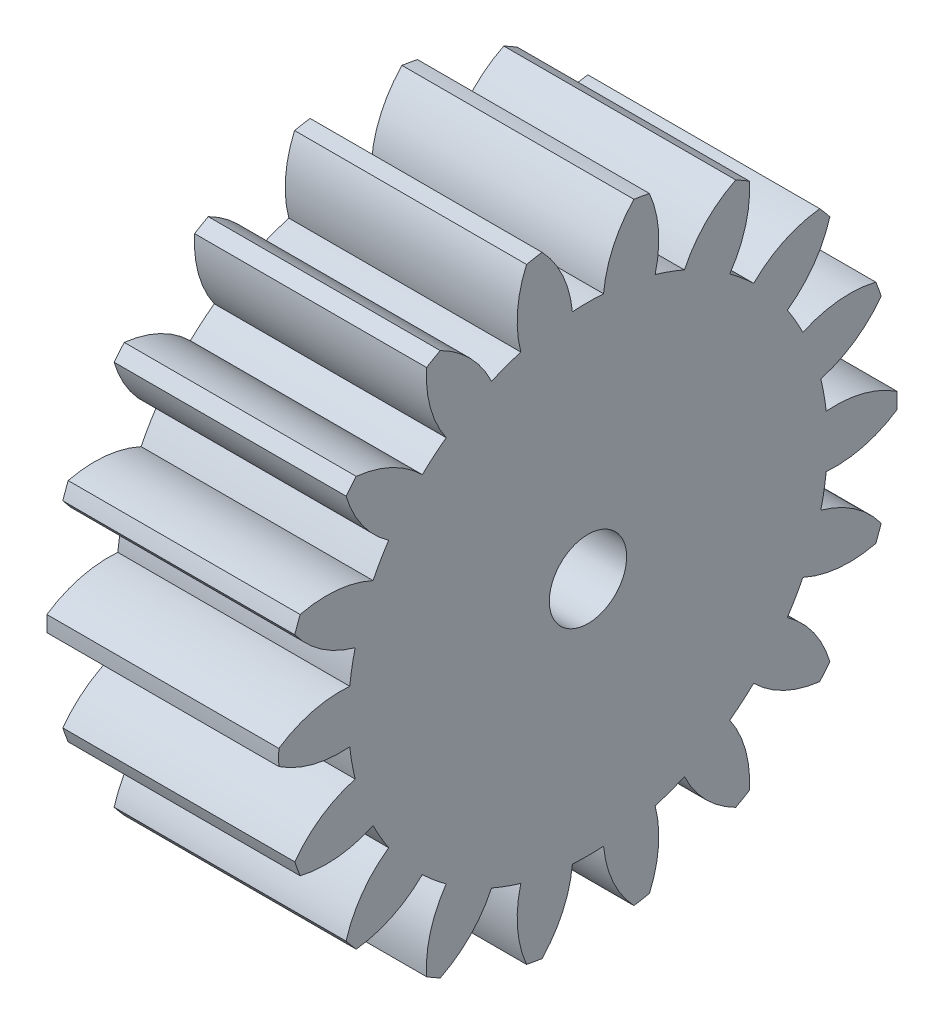
SolidWorks part; units mm, degrees
ref_plane "Plane1" through (0, 0, 0) normal (0, 0, 1) x (1, 0, 0)
ref_plane "Plane2" through (0, 0, 0) normal (0, 1, 0) x (1, 0, 0)
ref_plane "Plane3" through (0, 0, 0) normal (1, 0, 0) x (0, 0, -1)
other "Configuration Table"
sketch "HoldingSke" plane through (0, 0, 0) normal (0, 1, 0) x (1, 0, 0)
  line L0 (0, 0) -> (0.4755, -0.1545)
  line L1 (-15, 0) -> (100, 0) construction
  line L2 (0, 0) -> (-2.1039, 2.3779)
  line L3 (0, 0) -> (-11.863, 4.5341)
  line L4 (0, 0) -> (8.2133, 2.6687)
  line L5 (0, 0) -> (-46.8476, -17.4728)
  line L6 (0, 0) -> (-12.4344, -8.3896)
  line L7 (-2.1039, 2.3779) -> (8.6586, 51.2059)
  line L8 (-76.2, 54.61) -> (-75.3, 54.61)
  line L9 (-71.009, 38.7566) -> (-53.1078, 45.2721)
  line L10 (-76.2, 71.12) -> (104.1128, 71.12)
  line L11 (0, 0) -> (-15, 0)
  line L12 (-76.2, 101.6) -> (-76.133, 101.6)
  line L13 (24.9733, 27.94) -> (52.9518, 28.4284)
  line L14 (24.9733, 27.94) -> (24.9743, 27.94)
  line L15 (24.9733, 27.94) -> (100.4006, 29.5858)
  line L16 (-63.627, -2) -> (-12.827, -2)
  circle A0 centre (0, 0) radius 2.5
  circle A1 centre (0, 0) radius 15.499
  circle A2 centre (0, 0) radius 37.5
  circle A3 centre (0, 0) radius 2.5
  dimension "MHD" = 30.998
  dimension "Hub_dia" = 75
  dimension "Bore" = 5
  dimension "MBD" = 5
  dimension "Num_teeth" = 18
  dimension "Pitch" = 0.5
  dimension "Overall_len" = 50
  dimension "Show_teeth" = 18
  dimension "Thickness" = 15
  dimension "OAL" = 50.0001
  dimension "T_dim" = 0.9
  dimension "Ap" = 20
  dimension "H" = 19.05
  dimension "Pitch_radius" = 180.3128
  dimension "Width" = 15
  dimension "Backlash" = 0.067
  dimension "Addendum_fac" = 1
  dimension "Dedendum_fac" = 1.25
  dimension "Clearance_fac" = 0.25
  dimension "Dedendum_add" = 0.001
  dimension "Module" = 2
sketch "BasProSke" plane through (0, 0, 0) normal (0, 1, 0) x (1, 0, 0)
  line L0 (-10, 0) -> (60, 0) construction
  line L1 (0, 0) -> (0, 20)
  line L2 (0, 0) -> (15, 0)
  line L3 (15, 0) -> (15, 20)
  line L4 (15, 20) -> (0, 20)
  dimension "Thickness" = 15
  dimension "Diameter" = 40
revolve "Base-Revolve" add sketch "BasProSke" angle 360 about L0
sketch "TooCutSke" plane through (0, 0, 0) normal (1, 0, 0) x (0, 0, -1)
  line L1 (0, 0) -> (0, 107) construction
  line L2 (0, 0) -> (-1.686, 17.9209) construction
  line L3 (0, 0) -> (-6.231, 35.3376) construction
  line L4 (-1.686, 17.9209) -> (-3.1155, 17.6688) construction
  arc A0 (1.0078, 15.4662) -> (-1.0078, 15.4662) centre (0, 0) ccw
  arc A1 (2.9913, 19.8007) -> (-2.9913, 19.8007) centre (0, 0) ccw
  circle A2 centre (0, 0) radius 18 construction
  circle A3 centre (0, 0) radius 16.9145 construction
  arc A4 (-1.0078, 15.4662) -> (-2.9913, 19.8007) centre (-8.1775, 14.8063) ccw
  arc A5 (2.9913, 19.8007) -> (1.0078, 15.4662) centre (8.1775, 14.8063) ccw
  dimension "Root_dia" = 30.998
  dimension "Overcut_dia" = 40.0508
  dimension "Pitch_dia" = 36
  dimension "Base_dia" = 33.8289
  dimension "Flank_rad" = 7.2
  dimension "Half_ang" = 10
  dimension "Half_CT" = 1.4516
extrude "ToothCut" cut sketch "TooCutSke" along normal through all
fillet "Breaks" [suppressed] radius 0.04
fillet "RootFillets" [suppressed] radius 0.501
pattern_circular "TeethCuts" count 18 every 20 about axis through (-10, 0, 0) along (1, 0, 0) of "ToothCut", "RootFillets", "Breaks"
sketch "HubNeaOneSke" plane through (0, 0, 0) normal (-1, 0, 0) x (0, 0, 1)
  circle A0 centre (0, 0) radius 15.499
  dimension "Diameter" = 30.998
extrude "HubNearOne" [suppressed] add sketch "HubNeaOneSke" along normal blind 35.0001
sketch "HubNeaBotSke" plane through (0, 0, 0) normal (-1, 0, 0) x (0, 0, 1)
  circle A0 centre (0, 0) radius 15.499
  dimension "Diameter" = 30.998
extrude "HubNearBoth" [suppressed] add sketch "HubNeaBotSke" along normal blind 17.5
ref_plane "FarPln" through (15, 0, 0) normal (1, 0, 0) x (0, 0, -1)
sketch "HubFarSke" plane through (15, 0, 0) normal (1, 0, 0) x (0, 0, -1)
  circle A0 centre (0, 0) radius 15.499
  dimension "Diameter" = 30.998
extrude "HubFar" [suppressed] add sketch "HubFarSke" along normal blind 17.5
sketch "BorSke" plane through (0, 0, 0) normal (1, 0, 0) x (0, 0, -1)
  circle A0 centre (0, 0) radius 2.5
  dimension "Diameter" = 5
extrude "Bore" cut sketch "BorSke" along normal mid plane 100.0001
sketch "KeySke" plane through (0, 0, 0) normal (1, 0, 0) x (0, 0, -1)
  line L0 (-1, 0) -> (-1, 3.4)
  line L1 (-1, 3.4) -> (1, 3.4)
  line L2 (1, 3.4) -> (1, 0)
  line L3 (0, 0) -> (0, 34) construction
  line L4 (-1, 0) -> (1, 0)
  dimension "Offset" = 3.4
  dimension "Width" = 2
extrude "Keyway" [suppressed] cut sketch "KeySke" along normal mid plane 100.0001
pattern_circular "Keyway2" [suppressed] count 2 every 90 about axis through (-10, 0, 0) along (1, 0, 0)
equation "' \"Module@HoldingSke\" = 6.35"
equation "' \"Num_teeth@HoldingSke\" = 12"
equation "' \"Ap@HoldingSke\" =  20"
equation "' \"Ap@HoldingSke\" = 20"
equation "' \"Width@HoldingSke\" = 0.5 * 25.4"
equation "' \"Hub_dia@HoldingSke\"= 1 * 25.4"
equation "' \"Hub_dia@HoldingSke\" = 1 * 25.4"
equation "' \"Overall_len@HoldingSke\" = 1.0 * 25.4"
equation "' \"Bore@HoldingSke\" = 0.75 * 25.4"
equation "' \"T_dim@HoldingSke\" = 0.1 * 25.4"
equation "' \"Width@KeySke\" = 0.25 * 25.4"
equation "' \"Show_teeth@HoldingSke\" = 13"
equation "' \"Backlash@HoldingSke\" = 0.009 * 25.4"
equation "' \"Addendum_fac@HoldingSke\" = 1.0"
equation "' \"Dedendum_fac@HoldingSke\" = 1.25"
equation "' \"Dedendum_add@HoldingSke\" = 0.00005 * 25.4"
equation "' \"Clearance_fac@HoldingSke\" = 0.25"
equation "\"Pitch@HoldingSke\" = 1 / \"Module@HoldingSke\""
equation "\"Overcut_dia@TooCutSke\" = (\"Num_teeth@HoldingSke\" + 2 * \"Addendum_fac@HoldingSke\") / \"Pitch@HoldingSke\" + 0.002 * 25.4"
equation "\"Pitch_dia@TooCutSke\" = \"Num_teeth@HoldingSke\" / \"Pitch@HoldingSke\""
equation "\"Base_dia@TooCutSke\" = \"Num_teeth@HoldingSke\" / \"Pitch@HoldingSke\" * cos((\"Ap@HoldingSke\"  * 3.14159265 / 180))"
equation "\"Root_dia@TooCutSke\" = (\"Num_teeth@HoldingSke\" + 2) / \"Pitch@HoldingSke\" - 2 * (\"Addendum_fac@HoldingSke\" + \"Dedendum_fac@HoldingSke\") / \"Pitch@HoldingSke\" - \"Dedendum_add@HoldingSke\" * 2"
equation "\"Half_ang@TooCutSke\" = 180 / \"Num_teeth@HoldingSke\""
equation "\"Half_CT@TooCutSke\" = \"Num_teeth@HoldingSke\" / \"Pitch@HoldingSke\" * sin((3.14159265 / 2 / \"Num_teeth@HoldingSke\")) / 2 - 7 * \"Backlash@HoldingSke\" / 4"
equation "\"Flank_rad@TooCutSke\" = \"Num_teeth@HoldingSke\" / \"Pitch@HoldingSke\" / 5"
equation "\"Radius@RootFillets\" = \"Clearance_fac@HoldingSke\" / \"Pitch@HoldingSke\" + \"Dedendum_add@HoldingSke\""
equation "\"Break_rad@Breaks\" = 0.02 / \"Pitch@HoldingSke\""
equation "\"Thickness@HoldingSke\" = \"Width@HoldingSke\""
equation "\"OAL@HoldingSke\" = \"Thickness@HoldingSke\""
equation "\"MHD@HoldingSke\" = (\"Num_teeth@HoldingSke\" + 2) / \"Pitch@HoldingSke\" - 2 * (\"Addendum_fac@HoldingSke\" + \"Dedendum_fac@HoldingSke\")  / \"Pitch@HoldingSke\" - \"Dedendum_add@HoldingSke\" * 2"
equation "\"MBD@HoldingSke\" = (\"Num_teeth@HoldingSke\" + 2) / \"Pitch@HoldingSke\" - 2 * (\"Addendum_fac@HoldingSke\" + \"Dedendum_fac@HoldingSke\")  / \"Pitch@HoldingSke\" - \"Dedendum_add@HoldingSke\" * 2 - 0.002 * 25.4"
equation "\"MHD@HoldingSke\" = ((sgn( \"MHD@HoldingSke\" - \"Hub_dia@HoldingSke\" )-1)*( \"MHD@HoldingSke\" - \"Hub_dia@HoldingSke\" ))/-2+ \"Hub_dia@HoldingSke\""
equation "\"MBD@HoldingSke\" = ((sgn( \"MBD@HoldingSke\" - \"Bore@HoldingSke\" )-1)*( \"MBD@HoldingSke\" - \"Bore@HoldingSke\" ))/-2+ \"Bore@HoldingSke\""
equation "\"OAL@HoldingSke\" = ((sgn( \"OAL@HoldingSke\" - \"Overall_len@HoldingSke\" )+1)*( \"OAL@HoldingSke\" - \"Overall_len@HoldingSke\" ))/2 + \"Overall_len@HoldingSke\" + 0.000002 * 25.4"
equation "\"Num_teeth@TeethCuts\" = int( \"Show_teeth@HoldingSke\" ) + 1"
equation "\"Num_teeth@TeethCuts\" = ((sgn( \"Num_teeth@TeethCuts\" - \"Num_teeth@HoldingSke\" )-1)*( \"Num_teeth@TeethCuts\" - \"Num_teeth@HoldingSke\" ))/-2+ \"Num_teeth@HoldingSke\""
equation "\"Num_teeth@TeethCuts\" = ((sgn( \"Num_teeth@TeethCuts\" - 2.0)+1)*( \"Num_teeth@TeethCuts\" - 2.0))/2 +2.0"
equation "\"Angle@TeethCuts\" = 360.0 / \"Num_teeth@HoldingSke\""
equation "\"Diameter@BasProSke\" = (\"Num_teeth@HoldingSke\" + 2 * \"Addendum_fac@HoldingSke\") / \"Pitch@HoldingSke\""
equation "\"Thickness@BasProSke\"  = \"Thickness@HoldingSke\""
equation "' \"Fillet_rad@BasProSke\" =  \"Thickness@HoldingSke\" * 0.05"
equation "' \"Fillet_rad@BasProSke\" = \"Thickness@HoldingSke\" * 0.05"
equation "\"MHD@HoldingSke\" = ((sgn( \"MHD@HoldingSke\" - \"Root_dia@TooCutSke\" )-1)*( \"MHD@HoldingSke\" - \"Root_dia@TooCutSke\" ))/-2+ \"Root_dia@TooCutSke\""
equation "\"Diameter@HubNeaOneSke\" = \"MHD@HoldingSke\""
equation "\"Length@HubNearOne\" = \"OAL@HoldingSke\" - \"Thickness@BasProSke\""
equation "\"Diameter@HubNeaBotSke\" = \"MHD@HoldingSke\""
equation "\"Length@HubNearBoth\" = ( \"OAL@HoldingSke\" - \"Thickness@BasProSke\" ) / 2.0"
equation "\"Thickness@FarPln\" = \"Thickness@BasProSke\""
equation "\"Diameter@HubFarSke\" = \"MHD@HoldingSke\""
equation "\"Length@HubFar\" = ( \"OAL@HoldingSke\" - \"Thickness@BasProSke\" ) / 2.0"
equation "\"Diameter@BorSke\" = \"MBD@HoldingSke\""
equation "\"D1@Bore\" = \"OAL@HoldingSke\" * 2.0"
equation "\"D1@Keyway\" = \"OAL@HoldingSke\" * 2.0"
equation "\"Offset@KeySke\" = \"T_dim@HoldingSke\" + \"MBD@HoldingSke\" / 2.0"
